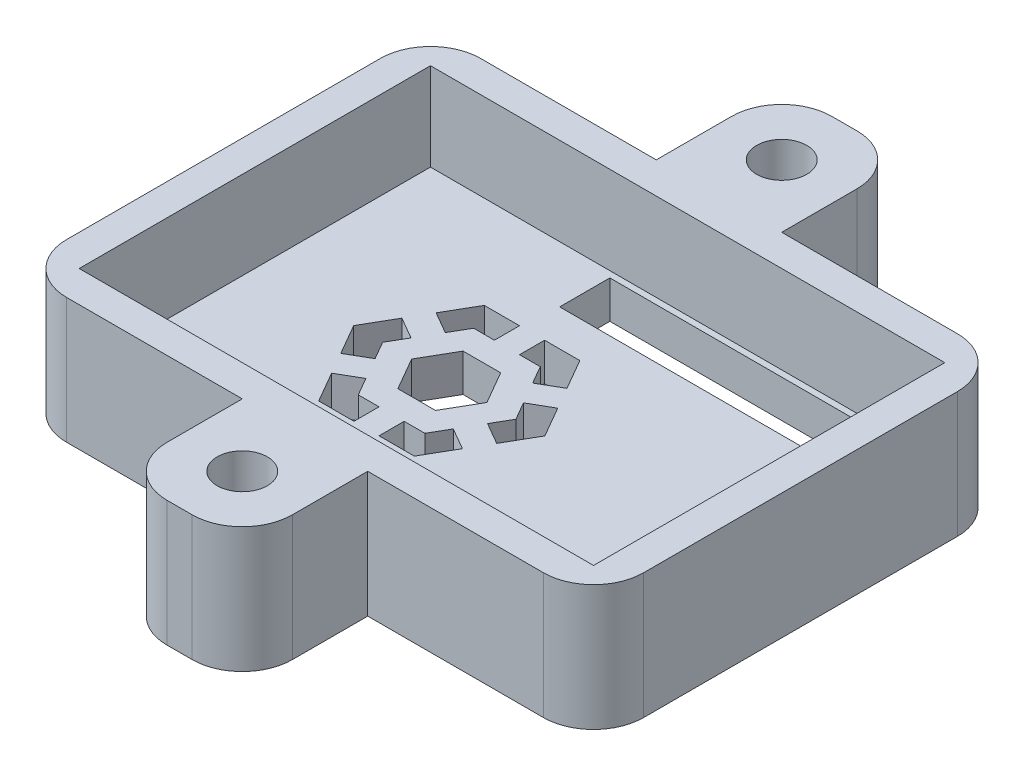
SolidWorks part; units mm, degrees
other "Markup1"
sketch "Sketch12"
other "Markup2"
sketch "Sketch13" plane through (-23, 10, -26.5) normal (-0.0482, 0.997, -0.0606) x (-0.0179, -0.0615, -0.9979)
ref_plane "Front Plane" through (0, 0, 0) normal (0, 0, 1) x (1, 0, 0)
ref_plane "Top Plane" through (0, 0, 0) normal (0, 1, 0) x (1, 0, 0)
ref_plane "Right Plane" through (0, 0, 0) normal (1, 0, 0) x (0, 0, -1)
sketch "Base" plane through (0, 0, 0) normal (0, 1, 0) x (1, 0, 0)
  line L1 (23, 16.5) -> (-23, 16.5)
  line L2 (23, 16.5) -> (23, -16.5)
  line L3 (23, -16.5) -> (-23, -16.5)
  line L4 (-23, 16.5) -> (-23, -16.5)
  line L5 (23, 16.5) -> (-23, -16.5) construction
  line L6 (23, -16.5) -> (-23, 16.5) construction
  point P0 (0, 0)
  dimension "D1" = 33
  dimension "D2" = 46
extrude "Shell" add sketch "Base" along normal blind 10
sketch "PinHoles" plane through (0, 0, 0) normal (0, -1, 0) x (-1, 0, 0)
  line L0 (-23, 0) -> (23, 0) construction
  line L2 (20, -13.5) -> (-20, -13.5) construction
  line L3 (0, 16.5) -> (0, -16.5) construction
  line L4 (20, -13.5) -> (20, 13.5) construction
  line L5 (20, 13.5) -> (-20, 13.5) construction
  line L6 (-17.3, 9.5) -> (5.7, 13.5) construction
  line L7 (-17.3, -13.5) -> (5.7, -13.5)
  line L8 (-17.3, -13.5) -> (-17.3, -9.5)
  line L9 (-17.3, -9.5) -> (5.7, -9.5)
  line L10 (5.7, -13.5) -> (5.7, -9.5)
  line L11 (-17.3, -13.5) -> (5.7, -9.5) construction
  line L12 (-17.3, -9.5) -> (5.7, -13.5) construction
  line L13 (-17.3, 13.5) -> (5.7, 9.5) construction
  line L14 (5.7, 13.5) -> (5.7, 9.5)
  line L15 (-17.3, 9.5) -> (5.7, 9.5)
  line L16 (-17.3, 13.5) -> (-17.3, 9.5)
  line L17 (-17.3, 13.5) -> (5.7, 13.5)
  line L18 (23, 16.5) -> (23, -16.5) construction
  line L19 (-23, -16.5) -> (-23, 16.5) construction
  line L20 (23, -16.5) -> (-23, -16.5) construction
  line L21 (-23, 16.5) -> (23, 16.5) construction
  line L22 (-20, -13.5) -> (-20, 13.5) construction
  line L23 (20, -13.5) -> (-20, 13.5) construction
  line L24 (20, 13.5) -> (-20, -13.5) construction
  point P2 (0, 0)
  point P12 (-5.8, -11.5)
  point P21 (-5.8, 11.5)
  dimension "D3" = 4
  dimension "D4" = 23
  dimension "D1" = 3
  dimension "D2" = 40
  dimension "D5" = 27
  dimension "D6" = 2.7
sketch "ShellHole" plane through (0, 10, 0) normal (0, 1, 0) x (1, 0, 0)
  line L1 (-20.5, 14) -> (20.5, 14)
  line L2 (-20.5, 14) -> (-20.5, -14)
  line L3 (-20.5, -14) -> (20.5, -14)
  line L4 (20.5, 14) -> (20.5, -14)
  line L5 (-20.5, 14) -> (20.5, -14) construction
  line L6 (-20.5, -14) -> (20.5, 14) construction
  point P0 (0, 0)
  dimension "D1" = 41
  dimension "D2" = 28
extrude "Hole" cut sketch "ShellHole" against normal blind 7
extrude "Pins" cut sketch "PinHoles" against normal blind 3
sketch "Sketch10" plane through (0, 0, 16.5) normal (0, 0, 1) x (1, 0, 0)
  line L0 (-23, 10) -> (23, 10) construction
  line L1 (-5, 0) -> (5, 0)
  line L2 (-5, 0) -> (-5, 10)
  line L3 (-5, 10) -> (5, 10)
  line L4 (5, 0) -> (5, 10)
  line L5 (-5, 0) -> (5, 10) construction
  line L6 (-5, 10) -> (5, 0) construction
  line L7 (-23, 10) -> (-23, 0) construction
  point P0 (0, 5)
  dimension "D1" = 10
  dimension "D2" = 10
  dimension "D3" = 23
extrude "Boss-Extrude3" add sketch "Sketch10" along normal blind 10
sketch "Sketch11" plane through (0, 10, 0) normal (0, 1, 0) x (1, 0, 0)
  line L0 (-5, -21.5) -> (5, -21.5) construction
  line L1 (-5, -26.5) -> (-5, -16.5) construction
  line L2 (5, -26.5) -> (5, -16.5) construction
  line L3 (0, -26.5) -> (0, -14) construction
  line L4 (5, -26.5) -> (-5, -26.5) construction
  line L5 (-20.5, -14) -> (20.5, -14) construction
  circle A0 centre (0, -21.5) radius 2
  dimension "D1" = 4
extrude "Cut-Extrude3" cut sketch "Sketch11" against normal blind 10
fillet "Fillet1" radius 4 2 edges at (5, 5, 26.5) (-5, 5, 26.5)
mirror "Mirror1" about plane through (0, 0, 0) normal (0, 0, 1) of "Cut-Extrude3", "Fillet1", "Boss-Extrude3"
fillet "Fillet2" radius 4 4 edges at (23, 5, 16.5) (-23, 5, 16.5) (-23, 5, -16.5) (23, 5, -16.5)
sketch "AirHole" plane through (0, 3, 0) normal (0, 1, 0) x (1, 0, 0)
  line L0 (-5, 6.5981) -> (-5, -6.5981) construction
  line L1 (-8, 0) -> (-6.5, -2.5981)
  line L2 (-6.5, -2.5981) -> (-3.5, -2.5981)
  line L3 (-3.5, -2.5981) -> (-2, 0)
  line L4 (-2, 0) -> (-3.5, 2.5981)
  line L5 (-3.5, 2.5981) -> (-6.5, 2.5981)
  line L6 (-6.5, 2.5981) -> (-8, 0)
  line L7 (-10.3094, 0) -> (-7.6547, -4.5981)
  line L8 (-7.6547, -4.5981) -> (-2.3453, -4.5981)
  line L9 (-2.3453, -4.5981) -> (0.3094, 0)
  line L10 (0.3094, 0) -> (-2.3453, 4.5981)
  line L11 (-2.3453, 4.5981) -> (-7.6547, 4.5981)
  line L12 (-7.6547, 4.5981) -> (-10.3094, 0)
  line L21 (2.6188, 0) -> (-1.1906, 6.5981)
  line L22 (-1.1906, 6.5981) -> (-8.8094, 6.5981)
  line L23 (-8.8094, 6.5981) -> (-12.6188, 0)
  line L24 (-12.6188, 0) -> (-8.8094, -6.5981)
  line L25 (-8.8094, -6.5981) -> (-1.1906, -6.5981)
  line L26 (-1.1906, -6.5981) -> (2.6188, 0)
  line L27 (-12.6188, 0) -> (2.6188, 0) construction
  line L28 (-7.75, 0.433) -> (-11.2141, 2.433)
  line L29 (-6.75, 2.1651) -> (-10.2141, 4.1651)
  line L30 (-6.75, 2.1651) -> (-2.25, -0.433) construction
  line L31 (-7.75, 0.433) -> (-3.25, -2.1651) construction
  line L32 (-2.25, -0.433) -> (1.2141, -2.433)
  line L33 (-3.25, -2.1651) -> (0.2141, -4.1651)
  line L34 (-6, -2.5981) -> (-6, -6.5981)
  line L35 (-4, -2.5981) -> (-4, -6.5981)
  line L36 (-6, -2.5981) -> (-6, 2.5981) construction
  line L37 (-4, -2.5981) -> (-4, 2.5981) construction
  line L38 (-6, 2.5981) -> (-6, 6.5981)
  line L39 (-4, 2.5981) -> (-4, 6.5981)
  line L40 (-3.25, 2.1651) -> (0.2141, 4.1651)
  line L41 (-2.25, 0.433) -> (1.2141, 2.433)
  line L42 (-3.25, 2.1651) -> (-7.75, -0.433) construction
  line L43 (-2.25, 0.433) -> (-6.75, -2.1651) construction
  line L44 (-7.75, -0.433) -> (-11.2141, -2.433)
  line L45 (-6.75, -2.1651) -> (-10.2141, -4.1651)
  circle A0 centre (-5, 0) radius 2.5981 construction
  circle A1 centre (-5, 0) radius 4.5981 construction
  circle A2 centre (-5, 0) radius 6.5981 construction
  point P9 (-3.2515, 2.1676)
  dimension "D1" = 5
  dimension "D2" = 2
  dimension "D3" = 2
  dimension "D4" = 3
  dimension "D5" = 0.5
  dimension "D6" = 0.5
  dimension "D7" = 0.5
  dimension "D8" = 0.5
  dimension "D9" = 0.5
  dimension "D10" = 0.5
extrude "Air1" cut sketch "AirHole" against normal blind 10 contours L5 L6 L1 L2 L3 L4 | L11 L38 L22 L23 L29 L12 | L44 L7 L12 L28 L23 L24 | L7 L45 L24 L25 L34 L8 | L8 L35 L25 L26 L33 L9 | L41 L10 L9 L32 L26 L21 | L10 L40 L21 L22 L39 L11
equation "\"width\"= 2.7"
equation "\"height\"= 4.0"
equation "\"depthUp\"= 0.3"
equation "\"depthDown\"= 0.4"
equation "\"shellWidth\"= 0.6"
equation "\"shellHeight\"= 0.3"
equation "\"D2@Base\"= \"height\" + \"shellWidth\""
equation "\"D1@Base\"= \"width\" + \"shellWidth\""
equation "\"D1@Shell\"= \"depthUp\" + \"depthDown\" + \"shellHeight\""
equation "\"D4@PinHoles\"=2.3"
equation "\"D3@PinHoles\" = 0.4"
equation "\"D1@PinHoles\" = \"shellWidth\" / 2"
equation "\"D1@ShellHole\" = \"height\" + 0.1"
equation "\"D2@ShellHole\" = \"width\" + 0.1"
equation "\"D1@Hole\" = \"depthUp\" + \"depthDown\""
equation "\"D1@Pins\" = \"shellHeight\""
equation "\"D2@Sketch10\"= \"D1@Shell\""
equation "\"D3@Sketch10\"= \"D2@Base\" / 2"
